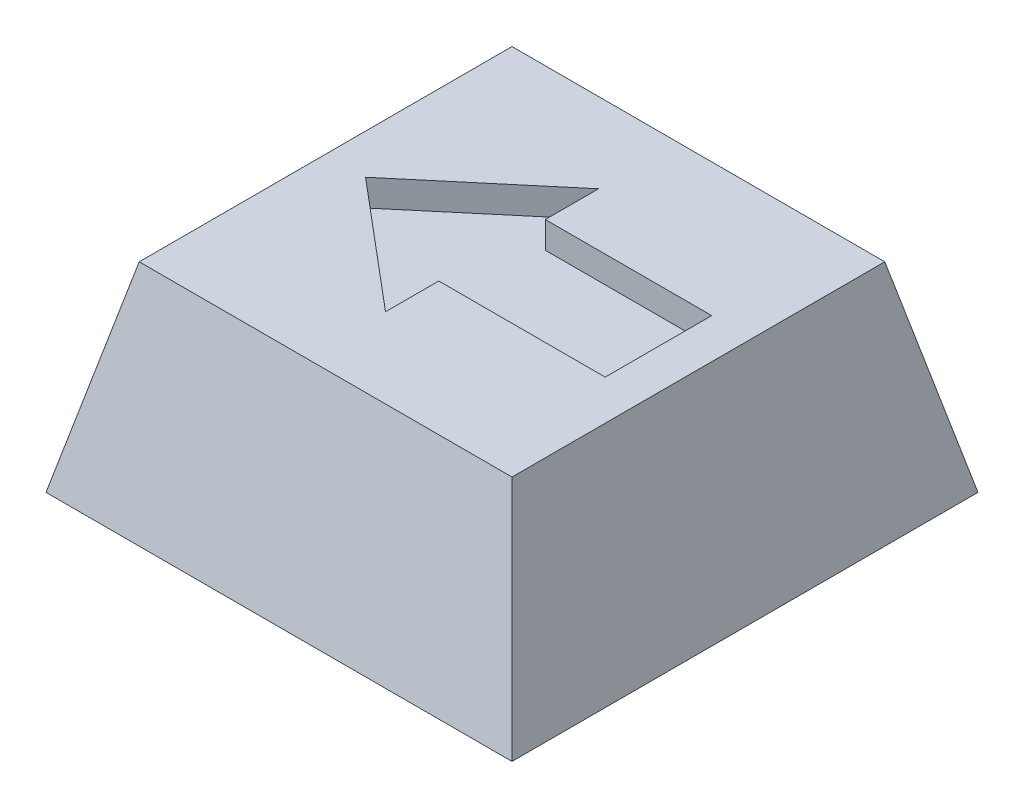
SolidWorks part; units mm, degrees
ref_plane "Front Plane" through (0, 0, 0) normal (0, 0, 1) x (1, 0, 0)
ref_plane "Top Plane" through (0, 0, 0) normal (0, 1, 0) x (1, 0, 0)
ref_plane "Right Plane" through (0, 0, 0) normal (1, 0, 0) x (0, 0, -1)
sketch "Sketch1" plane through (0, 0, 0) normal (0, 1, 0) x (1, 0, 0)
  line L1 (0, 0) -> (7, 0)
  line L2 (0, 0) -> (0, 7)
  line L3 (0, 7) -> (7, 7)
  line L4 (7, 0) -> (7, 7)
  dimension "D1" = 7
  dimension "D2" = 7
extrude "Boss-Extrude1" add sketch "Sketch1" along normal blind 3
sketch "Sketch2" plane through (0, 0, 0) normal (0, 0, 1) x (1, 0, 0)
  line L0 (0, 0) -> (0.7, 3)
  line L1 (0, 3) -> (7, 3) construction
  line L2 (0.7, 3) -> (0, 3)
  line L3 (0, 3) -> (0, 0)
  line L4 (7, 0) -> (6.3, 3)
  line L5 (6.3, 3) -> (7, 3)
  line L6 (7, 3) -> (7, 0)
  dimension "D1" = 0.7
  dimension "D2" = 0.7
extrude "Cut-Extrude1" cut sketch "Sketch2" against normal blind 7
sketch "Sketch3" plane through (0, 0, 0) normal (1, 0, 0) x (0, 0, -1)
  line L0 (0, 0) -> (0.7, 3)
  line L1 (7, 3) -> (0, 3) construction
  line L2 (0.7, 3) -> (0, 3)
  line L3 (0, 3) -> (0, 0)
  line L4 (7, 3) -> (6.3, 3)
  line L5 (6.3, 3) -> (7, 0)
  line L6 (7, 3) -> (7, 0)
  dimension "D1" = 0.7
  dimension "D2" = 0.7
extrude "Cut-Extrude2" cut sketch "Sketch3" along normal blind 11
sketch "Sketch4" plane through (0, 0, 0) normal (0, -1, 0) x (1, 0, 0)
  line L0 (3.5, 0) -> (3.5, -7) construction
  line L1 (0, 0) -> (7, 0) construction
  line L2 (7, -7) -> (0, -7) construction
  line L3 (0, -3.5) -> (7, -3.5) construction
  line L4 (0, -7) -> (0, 0) construction
  line L5 (7, 0) -> (7, -7) construction
  circle A0 centre (3.5, -3.5) radius 1.8
  dimension "D1" = 3.6
extrude "Cut-Extrude3" cut sketch "Sketch4" against normal blind 0.8
sketch "Sketch5" plane through (0, 3, 0) normal (0, 1, 0) x (1, 0, 0)
  line L0 (6.3, 6.3) -> (0.7, 6.3) construction
  line L1 (5.7, 4.3) -> (3.2, 4.3)
  line L2 (5.7, 4.3) -> (5.7, 2.7)
  line L3 (5.7, 2.7) -> (3.2, 2.7)
  line L4 (3.2, 4.3) -> (3.2, 2.7)
  line L5 (6.3, 0.7) -> (0.7, 0.7) construction
  line L6 (6.3, 6.3) -> (6.3, 0.7) construction
  line L7 (3.2, 4.3) -> (3.2, 5.1)
  line L8 (3.2, 5.1) -> (1.3, 3.5)
  line L9 (1.3, 3.5) -> (3.2, 1.9)
  line L10 (3.2, 1.9) -> (3.2, 2.7)
  line L11 (0.7, 6.3) -> (0.7, 0.7) construction
  dimension "D1" = 2
  dimension "D2" = 2
  dimension "D3" = 0.6
  dimension "D4" = 0.6
  dimension "D5" = 2.5
  dimension "D6" = 0.8
  dimension "D7" = 0.8
extrude "Cut-Extrude4" cut sketch "Sketch5" against normal blind 0.4 contours L1 L4 L3 L2 | L9 L10 L4 L7 L8
